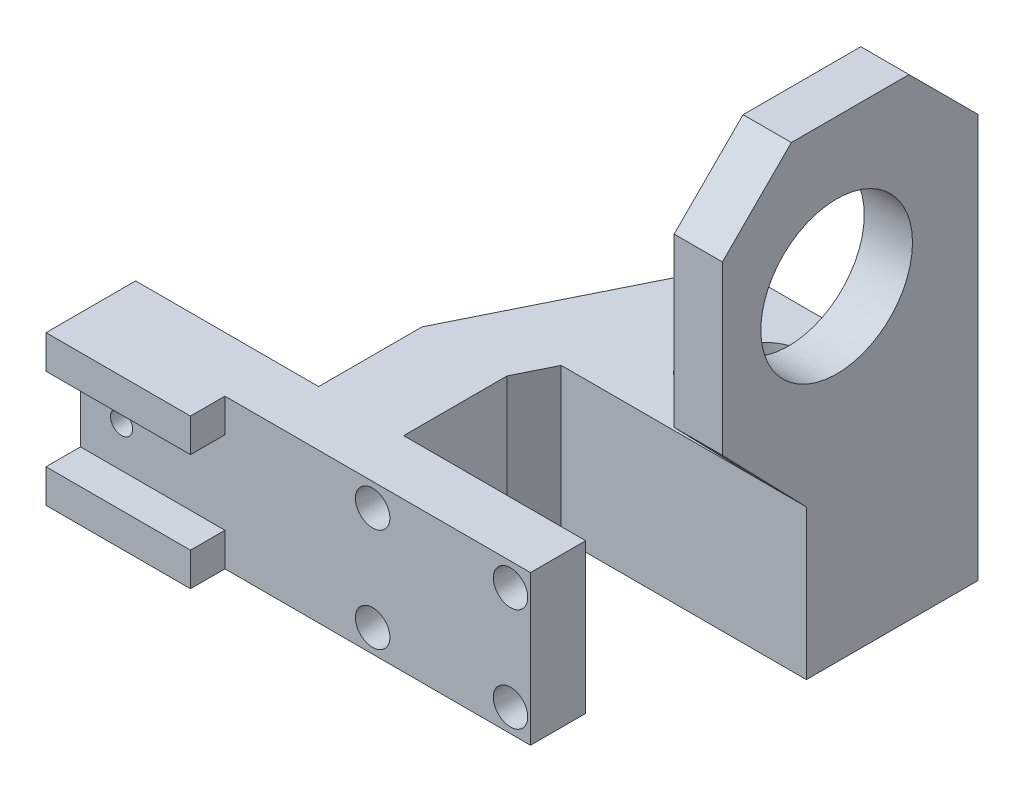
SolidWorks part; units mm, degrees
ref_plane "Přední rovina" through (0, 0, 0) normal (0, 0, 1) x (1, 0, 0)
ref_plane "Horní rovina" through (0, 0, 0) normal (0, 1, 0) x (1, 0, 0)
ref_plane "Pravá rovina" through (0, 0, 0) normal (1, 0, 0) x (0, 0, -1)
sketch "Skica1" plane through (0, 0, 0) normal (0, 0, 1) x (1, 0, 0)
  line L1 (16.212, -19.9414) -> (-34.0669, -19.9414)
  line L2 (16.212, -19.9414) -> (16.212, 1.7586)
  line L3 (16.212, 1.7586) -> (-34.0669, 1.7586)
  line L4 (-34.0669, -19.9414) -> (-34.0669, 1.7586)
  circle A0 centre (13.312, -16.5914) radius 1.6
  circle A1 centre (-6.688, -16.5914) radius 1.6
  circle A2 centre (-6.688, -1.5914) radius 1.6
  circle A3 centre (13.312, -1.5914) radius 1.6
  dimension "D1" = 3.2
  dimension "D2" = 2
  dimension "D3" = 2
extrude "Přidat vysunutím1" add sketch "Skica1" along normal blind 8
sketch "Skica2" plane through (0, 0, 8) normal (0, 0, 1) x (1, 0, 0)
  circle A0 centre (13.312, -16.5914) radius 2.5
  circle A1 centre (-6.688, -16.5914) radius 2.5
  circle A2 centre (-6.688, -1.5914) radius 2.5
  circle A3 centre (13.312, -1.5914) radius 2.5
  dimension "D1" = 5
  dimension "D2" = 2
  dimension "D3" = 2
extrude "Odebrat vysunutím1" cut sketch "Skica2" against normal blind 4
sketch "Skica4" plane through (0, 0, 0) normal (0, 0, -1) x (-1, 0, 0)
  line L0 (-16.212, 1.7586) -> (34.0669, 1.7586) construction
  line L1 (10.188, 1.7586) -> (22.5157, 1.7586)
  line L2 (10.188, 1.7586) -> (10.188, -19.9414)
  line L3 (10.188, -19.9414) -> (22.5157, -19.9414)
  line L4 (22.5157, 1.7586) -> (22.5157, -19.9414)
  line L5 (10.188, 1.7586) -> (10.188, -19.9414) construction
  line L6 (34.0669, -19.9414) -> (-16.212, -19.9414) construction
  line L7 (10.188, -19.9414) -> (10.188, 1.7586) construction
extrude "Přidat vysunutím2" add sketch "Skica4" along normal blind 15
sketch "Skica6" plane through (0, 1.7586, 0) normal (0, 1, 0) x (1, 0, 0)
  line L0 (-10.188, 15) -> (-22.5157, 15)
  line L1 (-10.188, 15) -> (-7.5858, 20.255)
  line L2 (-22.5157, 15) -> (-7.5858, 45.15)
  line L3 (4.7419, 45.15) -> (-7.5858, 45.15)
  line L5 (-7.5858, 45.15) -> (20.9737, 45.15)
  line L7 (-7.5858, 20.255) -> (20.9737, 20.255)
  line L8 (20.9737, 45.15) -> (20.9737, 20.255)
  circle A0 centre (8.2082, 34.15) radius 11 construction
  circle A3 centre (8.2082, 34.15) radius 5.4063
  line M11 (-10.188, 15) -> (-22.5157, 15)
extrude "Přidat vysunutím3" add sketch "Skica6" against normal up to surface (21.7 mm away) contours L8 L5 L3 L2 L1 L7 A3 M11 up to face at (-12.6397, -19.9414, -1.75)
sketch "Skica7" plane through (0, -19.9414, 0) normal (0, -1, 0) x (1, 0, 0)
  line L0 (8.2082, -34.15) -> (0.2082, -34.15) construction
  line L1 (8.2082, -34.15) -> (2.5514, -28.4931) construction
  line L2 (8.2082, -34.15) -> (13.8651, -39.8069) construction
  circle A0 centre (8.2082, -34.15) radius 8 construction
  circle A1 centre (2.5514, -28.4931) radius 1.5
  circle A2 centre (13.8651, -39.8069) radius 1.5
  point P12 (8.2082, -34.15)
  dimension "D1" = 16
  dimension "D2" = 3
  dimension "D3" = 2
extrude "Odebrat vysunutím3" cut sketch "Skica7" against normal up to surface (21.7 mm away) up to face at (-6.1951, 1.7586, -12.0675)
sketch "Skica8" plane through (-34.0669, 0, 0) normal (-1, 0, 0) x (0, 0, 1)
  line L4 (0, 1.7586) -> (0, -19.9414)
  line L5 (0, -19.9414) -> (8, -19.9414)
  line L6 (8, -19.9414) -> (8, 1.7586)
  line L7 (8, 1.7586) -> (0, 1.7586)
  line L8 (0, 1.7586) -> (0, -19.9414)
  line L9 (0, -19.9414) -> (8, -19.9414)
  line L10 (8, -19.9414) -> (8, 1.7586)
  line L11 (8, 1.7586) -> (0, 1.7586)
  dimension "D1" = 0
extrude "Přidat vysunutím4" add sketch "Skica8" along normal blind 15
sketch "Skica9" plane through (0, 0, 8) normal (0, 0, 1) x (1, 0, 0)
  circle A0 centre (-43.1091, -9.0914) radius 1.6
  circle A1 centre (-243.1091, -9.0914) radius 1.6 construction
extrude "Odebrat vysunutím4" cut sketch "Skica9" against normal blind 15
sketch "Skica10" plane through (20.9737, 0, 0) normal (1, 0, 0) x (0, 0, -1)
  line L0 (8.0742, 14.3404) -> (20.255, 1.7586)
  line L1 (45.15, -19.9414) -> (20.255, -19.9414)
  line L2 (45.15, -19.9414) -> (45.15, 48.6222)
  line L3 (45.15, 48.6222) -> (8.0742, 48.6222)
  line L4 (8.0742, 14.3404) -> (8.0742, 48.6222)
  line L5 (20.255, 1.7586) -> (20.255, -19.9414)
  circle A0 centre (24.65, 27.2586) radius 11
  dimension "D1" = 22
extrude "Přidat vysunutím5" add sketch "Skica10" along normal blind 7
chamfer "Zkosení1" distance 10 angle 45 2 edges at (24.4737, 48.6222, -8.0742) (24.4737, 48.6222, -45.15)
sketch "Skica11" plane through (0, 0, 8) normal (0, 0, 1) x (1, 0, 0)
  line L0 (-49.0669, -19.9414) -> (16.212, -19.9414) construction
  line L1 (-28.1091, -3.0914) -> (-49.0669, -3.0914)
  line L3 (-28.1091, -15.0914) -> (-49.0669, -15.0914)
  line L7 (-49.0669, 1.7586) -> (-28.1091, 1.7586)
  line L8 (-49.0669, 1.7586) -> (-49.0669, -3.0914)
  line L9 (-49.0669, -19.9414) -> (-28.1091, -19.9414)
  line L10 (-28.1091, 1.7586) -> (-28.1091, -3.0914)
  line L11 (-28.1091, -15.0914) -> (-28.1091, -19.9414)
  line L12 (-49.0669, -15.0914) -> (-49.0669, -19.9414)
  point P0 (-43.1091, -9.0914)
extrude "Přidat vysunutím6" add sketch "Skica11" along normal blind 5
